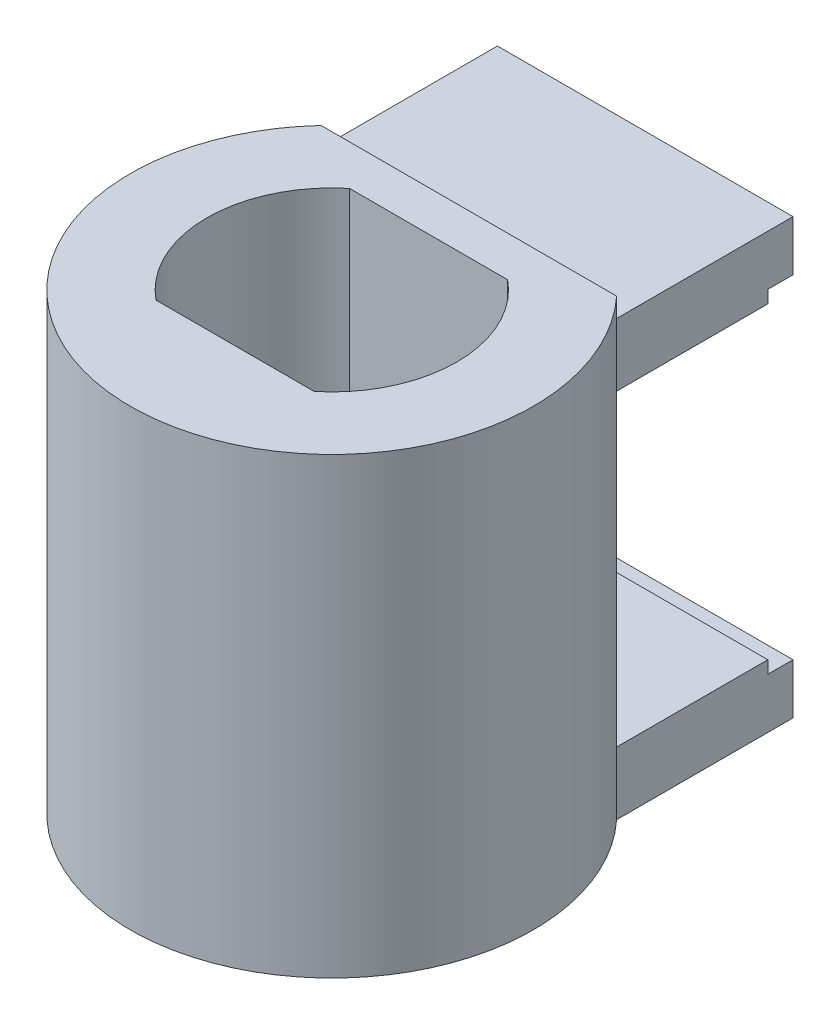
SolidWorks part; units mm, degrees
ref_plane "Front Plane" through (0, 0, 0) normal (0, 0, 1) x (1, 0, 0)
ref_plane "Top Plane" through (0, 0, 0) normal (0, 1, 0) x (1, 0, 0)
ref_plane "Right Plane" through (0, 0, 0) normal (1, 0, 0) x (0, 0, -1)
sketch "Sketch1" plane through (0, 0, 0) normal (0, 1, 0) x (1, 0, 0)
  circle A0 centre (0, 0) radius 2.9718
  circle A1 centre (0, 0) radius 4.7625
  dimension "D1" = 5.9436
  dimension "D2" = 9.525
extrude "Boss-Extrude1" add sketch "Sketch1" along normal blind 6.35
sketch "Sketch2" plane through (0, 6.35, 0) normal (0, 1, 0) x (1, 0, 0)
  circle A0 centre (0, 0) radius 2.9718
  circle A1 centre (0, 0) radius 12.7
  circle A2 centre (0, 0) radius 2.9718 construction
  dimension "D2" = 25.4
extrude "Boss-Extrude3" add sketch "Sketch2" along normal blind 3.175
sketch "Sketch3" plane through (0, 9.525, 0) normal (0, 1, 0) x (1, 0, 0)
  line L0 (-4.9838, 6.096) -> (4.9838, 6.096)
  line L1 (-4.9838, -6.096) -> (4.9838, -6.096)
  line L2 (0, 0) -> (50000, 0) construction
  arc A0 (-4.9838, 6.096) -> (-4.9838, -6.096) centre (0, 0) ccw
  circle A1 centre (0, 0) radius 12.7 construction
  circle A2 centre (0, 0) radius 12.7
  arc A3 (4.9838, -6.096) -> (4.9838, 6.096) centre (0, 0) ccw
  dimension "D1" = 15.748
  dimension "D2" = 12.192
extrude "Boss-Extrude4" add sketch "Sketch3" along normal blind 19.05
sketch "Sketch4" plane through (0, 6.35, 0) normal (0, -1, 0) x (1, 0, 0)
  line L0 (0, 0) -> (50000, 0) construction
  circle A0 centre (-4.3994, -0.635) radius 1.143
  circle A1 centre (4.3994, 0.635) radius 1.143
  point P6 (0, 0)
  dimension "D3" = 2.286
  dimension "D2" = 4.445
  dimension "D4" = 0.635
  dimension "D1" = 2
extrude "Cut-Extrude1" cut sketch "Sketch4" against normal through all both and the other way through all
ref_plane "Plane1" through (0, 0, -8.636) normal (0, 0, 1) x (1, 0, 0)
sketch "Sketch5" plane through (0, 0, -8.636) normal (0, 0, 1) x (1, 0, 0)
  line L0 (-12.7, 28.575) -> (-12.7, 6.35) construction
  line L1 (12.7, 28.575) -> (-12.7, 28.575)
  line L2 (12.7, 28.575) -> (12.7, 0)
  line L3 (12.7, 0) -> (-12.7, 0)
  line L4 (-12.7, 28.575) -> (-12.7, 0)
  line L5 (-4.4182, 0) -> (4.7406, 0) construction
extrude "Cut-Extrude2" cut sketch "Sketch5" against normal through all
sketch "Sketch7" plane through (0, 6.35, 0) normal (0, -1, 0) x (1, 0, 0)
  line L1 (-9.3118, -8.636) -> (9.3118, -8.636)
  line L2 (-9.3118, -8.636) -> (9.3118, -8.636)
  arc A0 (-4.7406, 0.4559) -> (-4.4182, -1.7778) centre (-4.3994, -0.635) ccw construction
  arc A1 (9.3118, -8.636) -> (-9.3118, -8.636) centre (0, 0) ccw
  arc A2 (9.3118, -8.636) -> (-9.3118, -8.636) centre (0, 0) ccw
  arc A3 (-4.4182, -1.7778) -> (4.7406, -0.4559) centre (0, 0) ccw construction
  arc A4 (4.7406, -0.4559) -> (4.4182, 1.7778) centre (4.3994, 0.635) ccw construction
  arc A5 (4.4182, 1.7778) -> (-4.7406, 0.4559) centre (0, 0) ccw construction
  arc A6 (-4.7406, 0.4559) -> (-4.4182, -1.7778) centre (-4.3994, -0.635) ccw
  arc A7 (-4.4182, -1.7778) -> (4.7406, -0.4559) centre (0, 0) ccw
  arc A8 (4.7406, -0.4559) -> (4.4182, 1.7778) centre (4.3994, 0.635) ccw
  arc A9 (4.4182, 1.7778) -> (-4.7406, 0.4559) centre (0, 0) ccw
  dimension "D1" = 0
extrude "Boss-Extrude6" add sketch "Sketch7" along normal up to surface (6.35 mm away) up to face at (0, 0, 0)
sketch "Sketch8" plane through (0, 0, -8.636) normal (0, 0, -1) x (-1, 0, 0)
  line L0 (9.3118, 0) -> (9.3118, 28.575) construction
  line L1 (-9.3118, 0) -> (9.3118, 0)
  line L2 (-9.3118, 0) -> (-9.3118, 3.175)
  line L3 (-9.3118, 3.175) -> (9.3118, 3.175)
  line L4 (9.3118, 0) -> (9.3118, 3.175)
  line L5 (-9.3118, 28.575) -> (-9.3118, 0) construction
  line L6 (-9.3118, 27.3558) -> (9.3118, 27.3558)
  line L7 (-9.3118, 27.3558) -> (-9.3118, 24.1808)
  line L8 (-9.3118, 24.1808) -> (9.3118, 24.1808)
  line L9 (9.3118, 27.3558) -> (9.3118, 24.1808)
  dimension "D1" = 21.0058
  dimension "D2" = 3.175
extrude "Boss-Extrude7" add sketch "Sketch8" along normal blind 11.1125
sketch "Sketch9" plane through (0, 0, -8.636) normal (0, 0, -1) x (-1, 0, 0)
  line L0 (9.3118, 3.175) -> (9.3118, 24.1808) construction
  line L1 (-9.3118, 3.175) -> (9.3118, 3.175)
  line L2 (-9.3118, 3.175) -> (-9.3118, 3.9688)
  line L3 (-9.3118, 3.9688) -> (9.3118, 3.9688)
  line L4 (9.3118, 3.175) -> (9.3118, 3.9688)
  line L6 (-9.3118, 24.1808) -> (9.3118, 24.1808)
  line L7 (-9.3118, 24.1808) -> (-9.3118, 23.387)
  line L8 (-9.3118, 23.387) -> (9.3118, 23.387)
  line L9 (9.3118, 24.1808) -> (9.3118, 23.387)
  dimension "D1" = 0.7937
extrude "Boss-Extrude8" add sketch "Sketch9" along normal blind 9.525
